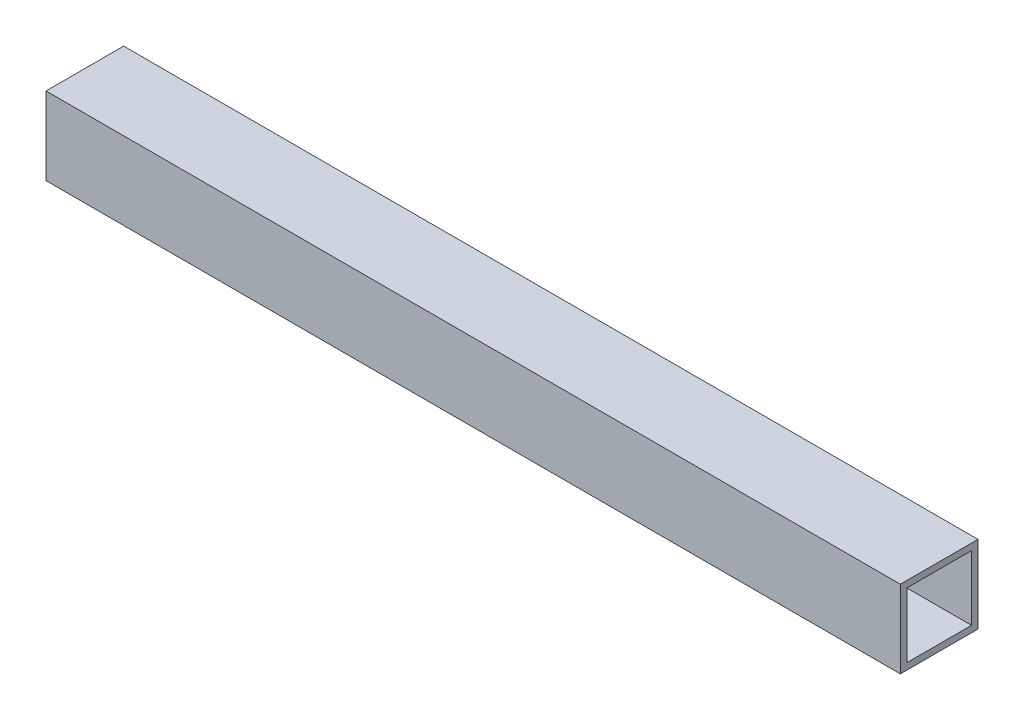
SolidWorks part; units mm, degrees
ref_plane "Front Plane" through (0, 0, 0) normal (0, 0, 1) x (1, 0, 0)
ref_plane "Top Plane" through (0, 0, 0) normal (0, 1, 0) x (1, 0, 0)
ref_plane "Right Plane" through (0, 0, 0) normal (1, 0, 0) x (0, 0, -1)
sketch "Sketch1" plane through (0, 0, 0) normal (1, 0, 0) x (0, -1, 0)
  line L1 (-9.525, 9.525) -> (9.525, 9.525)
  line L2 (-9.525, 9.525) -> (-9.525, -9.525)
  line L3 (-9.525, -9.525) -> (9.525, -9.525)
  line L4 (9.525, 9.525) -> (9.525, -9.525)
  line L5 (-9.525, 9.525) -> (9.525, -9.525) construction
  line L6 (-9.525, -9.525) -> (9.525, 9.525) construction
  line L7 (-7.9375, 7.9375) -> (7.9375, 7.9375)
  line L8 (-7.9375, 7.9375) -> (-7.9375, -7.9375)
  line L9 (-7.9375, -7.9375) -> (7.9375, -7.9375)
  line L10 (7.9375, 7.9375) -> (7.9375, -7.9375)
  line L11 (-7.9375, 7.9375) -> (7.9375, -7.9375) construction
  line L12 (-7.9375, -7.9375) -> (7.9375, 7.9375) construction
  point P0 (0, 0)
  point P5 (0, 0)
  dimension "D1" = 15.875
  dimension "D2" = 19.05
extrude "Boss-Extrude1" add sketch "Sketch1" along normal mid plane 209.55
sketch "Sketch3" plane through (0, -9.525, 0) normal (0, -1, 0) x (1, 0, 0)
  line L0 (104.775, 0) -> (58.025, 0) construction
  line L1 (104.775, 9.525) -> (104.775, -9.525) construction
  circle A0 centre (58.025, 0) radius 2.4257
  dimension "D2" = 4.8514
  dimension "D1" = 46.75
extrude "ShelfBarMountHole" cut sketch "Sketch3" against normal up to next
sketch "Sketch4" plane through (0, 0, -9.525) normal (0, 0, 1) x (1, 0, 0)
  line L2 (-66.675, 0) -> (73.025, 0) construction
  line L4 (73.025, 0) -> (114.3, 0) construction
  line L6 (104.775, -9.525) -> (104.775, 9.525) construction
  circle A0 centre (-66.675, 0) radius 2.4257
  circle A1 centre (73.025, 0) radius 2.4257
  dimension "D1" = 139.7
  dimension "D4" = 9.525
  dimension "D5" = 41.275
extrude "PowerSupply Mount Holes" cut sketch "Sketch4" along normal up to next
equation "\"Height\"= 32in"
equation "\"Width\"= 23in"
equation "\"Depth\"= 20in"
equation "\"Plexi\"= .121in"
equation "\"MagnetThickness\"=3mm"
equation "\"MagnetDiameter\"=12mm"
equation "\"DoorPlexi\" = \"Plexi\""
equation "\"BasePlateThickness\" = 0.5in"
equation "\"BasePlateWidth\" = \"Width\"+\"EBWidth\"-2*\"Plexi\""
equation "\"BasePlateDepth\" = \"Depth\"-\"Plexi\"-\"DoorPlexi\""
equation "\"Boxsize\" = .75in"
equation "\"BoxsizeHalf\" = \"Boxsize\"/2"
equation "\"Boxinner\" = .625in"
equation "\"CornerCube\" = 0.75in"
equation "\"FingerLength\" = 1.125in"
equation "\"FingerWidth\" = .625in"
equation "\"Cutwidth\"= .016in"
equation "\"Earsize\"= 1in + \"Cutwidth\" /2"
equation "\"Slotsize\" = 1in - \"CutWidth\" / 2"
equation "\"InnerWidth\" = \"Width\" - 2* \"Plexi\""
equation "\"InnerHeight\" = \"Height\" -2 * \"Plexi\""
equation "\"InnerDepth\" = \"Depth\" - 2*\"Plexi\""
equation "\"RearNumHoles\" = 7"
equation "\"RearHolesBorder\" = 2.2"
equation "\"RearHoleSpacing\" = (\"Width\" - 2*\"RearHolesBorder\") / (\"RearNumHoles\"-1)"
equation "\"RearBarLength\" = (\"InnerWidth\"-2*\"CornerCube\")"
equation "\"RearTopNumHoles\" = 6"
equation "\"RearTopHolesBorder\" = 2.5"
equation "\"RearTopHolesSpacing\" = (\"Width\" - 2*\"RearTopHolesBorder\") / (\"RearTopNumHoles\"-1)"
equation "\"SideTopNumHoles\" = 5"
equation "\"SideTopHoleOffset\"=\"CornerCube\"+\"FingerLength\"+\"Plexi\"+.5"
equation "\"SideHorizNumHoles\" = 6"
equation "\"SideHorizHoleBorder\" = 2.25"
equation "\"SideVertBarLength\"=\"Height\"-\"BasePlateThickness\"-2*\"CornerCube\"-\"Plexi\""
equation "\"SideVertNumHoles\" = 6"
equation "\"SideVertHolesBorder\" = \"CornerCube\"+\"FingerLength\"+.9"
equation "\"SideVertHoleSpacing\" = (\"InnerHeight\" - 2*\"SideVertHolesBorder\") / (\"SideVertNumHoles\"-1)"
equation "\"RearSideVertNumHoles\" = 7"
equation "\"RearSideVertHolesBorder\" = 2.5"
equation "\"RearSideVertHoleSpacing\" = (\"InnerHeight\" - 2*\"RearSideVertHolesBorder\") / (\"RearSideVertNumHoles\"-1)"
equation "\"RivetDia\" = .228in"
equation "\"SlotDepth\" = \"Plexi\" + 0.75in + .005in"
equation "\"SideSlotWidth\"   = \"Plexi\"+.005in"
equation "\"SidePanelVertSpacing\" = (\"Height\"-2*(1.75-\"Plexi\")) / 5"
equation "\"BottomPanelSideHoleSpacing\" = (\"InnerDepth\"-2*(1.75-\"Plexi\")) / 4"
equation "\"FrontDoorGap\" = .1in"
equation "\"TopDepth\" = \"Depth\"-\"DoorPlexi\"-\"FrontDoorGap\""
equation "\"TopBarDepth\" = \"Depth\"-\"DoorPlexi\"-\"Plexi\"-2*\"MagnetThickness\"-2*\"CornerCube\""
equation "\"CoolerDepth\" = 12in"
equation "\"ShelfDepth\" = \"TopBarDepth\"+\"CornerCube\"-\"CoolerDepth\""
equation "\"ShelfBarWidth\" = \"EBWidth\"-\"Boxsize\""
equation "\"ShelfGap\" = 0.5in"
equation "\"ShelfBarWidthShort\" = \"ShelfBarWidth\"-\"Boxsize\"-\"ShelfGap\""
equation "\"IntakeWidth\"=4in"
equation "\"IntakeHeight\"=2in"
equation "\"ExhaustWidth\"=4in"
equation "\"ExhaustHeight\"=2in"
equation "\"VentSpacing\"=7in"
equation "\"AngleBracketLength\"=20mm"
equation "\"AngleBracketWidth\"=10mm"
equation "\"AngleBracketThickness\"=1.5mm"
equation "\"AngleBracketHolePos\"=15mm"
equation "\"AngleBracketHoleDia\"=\"RivetDia\""
equation "\"ShelfBarAngleHole\"=\"ShelfGap\"+\"Boxsize\"+\"AngleBracketHolePos\""
equation "\"D1@Sketch3\"=\"ShelfBarAngleHole\""
equation "\"D2@Sketch3\"=\"Rivet3_16Dia\""
equation "\"D1@Boss-Extrude1\"=\"ShelfBarWidth\""
equation "\"SideTopHoleSpacing\" = (\"TopBarDepth\"-2*\"SideTopHoleOffset\") / (\"SideTopNumHoles\"-1)"
equation "\"SideHorizHoleSpacing\" = (\"TopBarDepth\"-2*\"SideHorizHoleBorder\") / (\"SideHorizNumHoles\"-1)"
equation "\"EBWidth\" = 9in"
equation "\"ShelfBarDepth\"=\"ShelfDepth\"-2*\"CornerCube\""
equation "\"ShelfWidth\" = \"EBWidth\"-\"ShelfGap\""
equation "\"D2@Sketch4\"=\"Rivet3_16Dia\""
equation "\"D4@Sketch4\"=\"BoxsizeHalf\""
equation "\"ComponentMountDia\"=0.1770"
equation "\"ShelfThickness\" = .220in"
equation "\"Rivet3_16Dia\" = .191in"
equation "\"BinderPostDia\" = .228in"
equation "\"ShelfHeight1\" = 13in"
equation "\"ShelfHeight2\" = 24in"
equation "\"VentVertLocation\"=12.75in"
equation "\"PSBracketThickness\" = .0641in"
equation "\"EBForwardMountOffset\" = 4.0in"
equation "\"EBForwardMount\" = 2*\"Boxsize\"+\"CoolerDepth\"+\"EBForwardMountOffset\""
equation "\"EBRearwardMountOffset\" = 1.5in"
equation "\"EBRearwardMount\"= \"Boxsize\"+\"EBRearwardMountOffset\""
